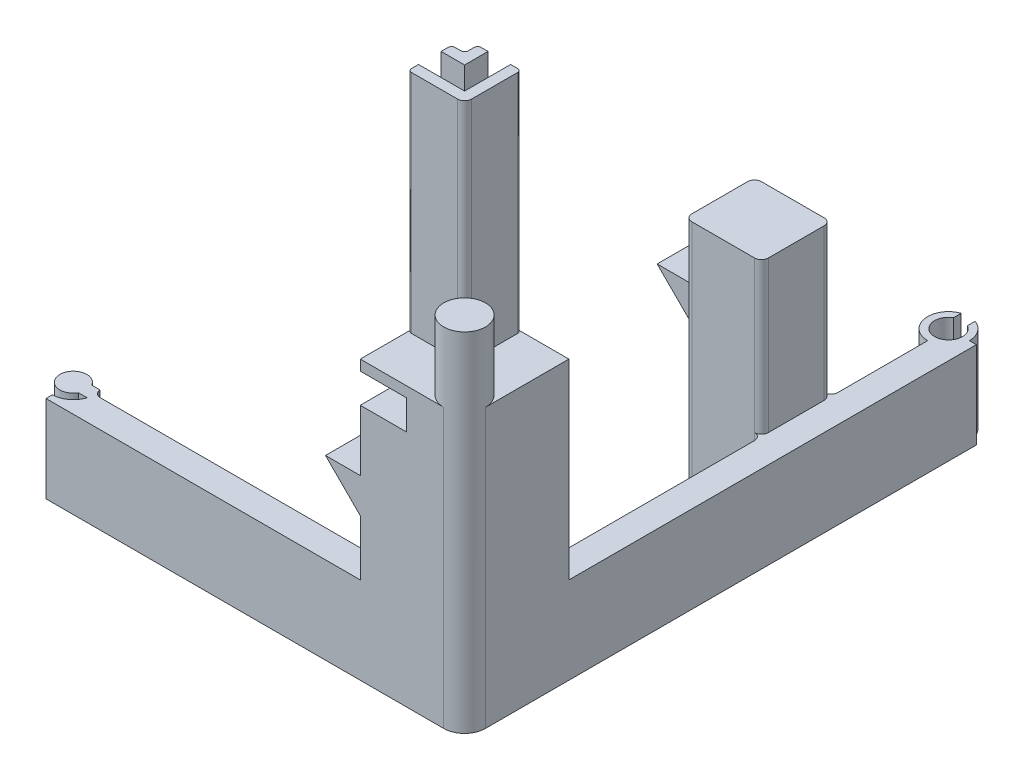
SolidWorks part; units mm, degrees
ref_plane "Front Plane" through (0, 0, 0) normal (0, 0, 1) x (1, 0, 0)
ref_plane "Top Plane" through (0, 0, 0) normal (0, 1, 0) x (1, 0, 0)
ref_plane "Right Plane" through (0, 0, 0) normal (1, 0, 0) x (0, 0, -1)
sketch "Sketch1" plane through (0, 0, 0) normal (0, 1, 0) x (1, 0, 0)
  line L1 (-15, -15) -> (15, -15)
  line L2 (-15, -15) -> (-15, 15)
  line L3 (-15, 15) -> (15, 15)
  line L4 (15, -15) -> (15, 15)
  line L5 (-15, -15) -> (15, 15) construction
  line L6 (-15, 15) -> (15, -15) construction
  point P0 (0, 0)
  dimension "D1" = 30
extrude "Boss-Extrude1" add sketch "Sketch1" along normal blind 80
sketch "Sketch2" plane through (0, 80, 0) normal (0, 1, 0) x (1, 0, 0)
  line L0 (-15, -15) -> (15, -15) construction
  line L1 (15, -15) -> (15, 15) construction
  circle A0 centre (9, -9) radius 6
  dimension "D1" = 12
extrude "Boss-Extrude2" add sketch "Sketch2" along normal blind 20
sketch "Sketch3" plane through (0, 80, 0) normal (0, 1, 0) x (1, 0, 0)
  line L2 (9, -15) -> (15, -15)
  line L4 (15, -15) -> (15, -9)
  circle A1 centre (9, -9) radius 6
  arc A4 (9, -15) -> (15, -9) centre (9, -9) ccw
  dimension "D1" = 0
extrude "Cut-Extrude1" cut sketch "Sketch3" against normal through all
sketch "Sketch4" plane through (0, 80, 0) normal (0, 1, 0) x (1, 0, 0)
  line L16 (-11.25, 1.75) -> (-1.75, 1.75)
  line L17 (-11.25, 11.25) -> (-8.25, 11.25) construction
  line L19 (-11.25, 11.25) -> (-11.25, 8.25) construction
  line L20 (-11.25, 8.25) -> (-8.25, 8.25)
  line L21 (-8.25, 11.25) -> (-8.25, 8.25)
  line L23 (-1.75, 1.75) -> (-1.75, 11.25)
  line L25 (-1.75, 11.25) -> (1.25, 11.25) construction
  line L26 (1.25, 11.25) -> (1.25, -1.25)
  line L27 (1.25, -1.25) -> (-11.25, -1.25)
  line L28 (-11.25, -1.25) -> (-11.25, 1.75) construction
  line L29 (-11.25, 1.75) -> (-11.25, 8.25) construction
  line L30 (-8.25, 11.25) -> (-1.75, 11.25) construction
  line L31 (-11.25, 11.25) -> (-11.25, 15) construction
  line L32 (15, 15) -> (-15, 15) construction
  line L33 (-11.25, 11.25) -> (-15, 11.25) construction
  line L34 (-15, 15) -> (-15, -15) construction
  line L35 (1.25, 11.25) -> (1.25, 15)
  line L36 (1.25, 15) -> (-1.75, 15)
  line L37 (-1.75, 15) -> (-1.75, 11.25)
  line L38 (-11.25, 1.75) -> (-15, 1.75)
  line L39 (-15, 1.75) -> (-15, -1.25)
  line L40 (-15, -1.25) -> (-11.25, -1.25)
  line L41 (-8.25, 11.25) -> (-8.25, 15)
  line L42 (-8.25, 15) -> (-11.25, 15)
  line L43 (-11.25, 15) -> (-11.25, 11.25)
  line L44 (-15, 11.25) -> (-15, 8.25)
  line L45 (-15, 8.25) -> (-11.25, 8.25)
  line L46 (-11.25, 11.25) -> (-15, 11.25)
  dimension "D1" = 6.5
  dimension "D2" = 3
  dimension "D3" = 3.75
extrude "Boss-Extrude3" add sketch "Sketch4" along normal blind 65
sketch "Sketch6" plane through (0, 0, 0) normal (0, -1, 0) x (1, 0, 0)
  line L1 (15, -15) -> (7, -15)
  line L2 (15, -15) -> (15, -132.175)
  line L3 (15, -132.175) -> (13, -132.175)
  line L4 (7, -15) -> (7, -126.175)
  arc A1 (7, -126.175) -> (13, -132.175) centre (7, -132.175) ccw
  dimension "D3" = 12
  dimension "D1" = 117.175
  dimension "D2" = 8
extrude "Boss-Extrude5" add sketch "Sketch6" against normal blind 2
sketch "Sketch7" plane through (0, 2, 0) normal (0, 1, 0) x (1, 0, 0)
  line L0 (7, 136.175) -> (7, 138.175) construction
  line L1 (9, 137.8319) -> (9, 135.6391)
  line L2 (5, 137.8319) -> (5, 135.6391)
  line L3 (7, 128.175) -> (7, 126.175) construction
  line L4 (15, 132.175) -> (13, 132.175)
  line L5 (15, 132.175) -> (15, 15)
  line L6 (15, 15) -> (7, 15)
  line L7 (7, 15) -> (7, 126.175) construction
  line L8 (15, 15) -> (1.25, 15) construction
  line L9 (7, 15) -> (7, 126.175)
  arc A0 (5, 137.8319) -> (7, 126.175) centre (7, 132.175) ccw
  arc A1 (13, 132.175) -> (7, 126.175) centre (7, 132.175) ccw construction
  arc A2 (5, 135.6391) -> (9, 135.6391) centre (7, 132.175) ccw
  arc A3 (13, 132.175) -> (9, 137.8319) centre (7, 132.175) ccw
  dimension "D1" = 2
  dimension "D2" = 2
extrude "Boss-Extrude6" add sketch "Sketch7" along normal offset from surface (23 mm away) 25 up to face at (3.75, 0, -48.4406)
sketch "Sketch9" plane through (0, 0, 0) normal (0, -1, 0) x (1, 0, 0)
  line L0 (15, -15) -> (7, -15) construction
  line L1 (-15, 15) -> (-105.5, 15) construction
  line L2 (-15, 15) -> (-15, 7)
  line L3 (-15, 7) -> (-99.5, 7) construction
  line L4 (-105.5, 15) -> (-105.5, 13.1746) construction
  line L5 (-109.375, 7) -> (-109.5, 7) construction
  line L6 (-101.5, 7) -> (-99.5, 7) construction
  line L7 (-99.5, 9) -> (-102.181, 9) construction
  line L8 (7, -136.175) -> (7, -138.175) construction
  line L9 (9, -137.8319) -> (5, -137.8319) construction
  line L10 (-99.5, 5) -> (-102.181, 5) construction
  line L11 (-99.5, 9) -> (-99.5, 5) construction
  line L12 (-102.1228, 8.9) -> (-99.625, 8.9)
  line L13 (-102.1228, 5.1) -> (-99.5, 5.1) construction
  line L14 (-99.5, 5.1) -> (-99.5, 7) construction
  line L15 (-99.5, 8.9) -> (-99.625, 8.9) construction
  line L16 (-105.375, 15) -> (-105.375, 13.1733)
  line L17 (-105.375, 14.0867) -> (-105.5, 14.0873) construction
  line L18 (-105.375, 15) -> (-15, 15)
  line L19 (-99.5, 5.1) -> (-99.5, 7) construction
  line L20 (-15, 7) -> (-99.5, 7)
  line L21 (-99.8088, 5.1) -> (-102.1228, 5.1)
  circle A0 centre (-105.5, 7) radius 4 construction
  arc A1 (9, -135.6391) -> (5, -135.6391) centre (7, -132.175) ccw construction
  arc A2 (-102.1228, 8.9) -> (-102.1228, 5.1) centre (-105.5, 7) ccw
  arc A4 (-99.625, 8.9) -> (-105.5, 13.1746) centre (-105.5, 7) ccw construction
  arc A6 (-99.625, 8.9) -> (-105.375, 13.1733) centre (-105.5, 7) ccw
  arc A7 (-99.8088, 5.1) -> (-99.5, 7) centre (-105.5, 7) ccw
  arc A8 (7, -126.175) -> (5, -137.8319) centre (7, -132.175) ccw construction
  dimension "D1" = 90.5
  dimension "D2" = 0.125
  dimension "D3" = 1.9
extrude "Boss-Extrude7" add sketch "Sketch9" against normal blind 25
fillet "Fillet1" radius 2 1 edges at (-99.5, 12.5, 7)
sketch "Sketch11" plane through (0, 0, 0) normal (0, -1, 0) x (1, 0, 0)
  line L0 (-99.625, 8.9) -> (-99.75, 8.9) construction
  line L2 (-99.625, 8.9) -> (-102.1228, 8.9) construction
  line L3 (-109.375, 7) -> (-109.5, 7) construction
  circle A0 centre (-105.5, 7) radius 6.0558
  arc A5 (-102.1228, 8.9) -> (-102.1228, 5.1) centre (-105.5, 7) ccw construction
extrude "Cut-Extrude2" cut sketch "Sketch11" against normal offset from surface (2.125 mm away) 0.125 up to face at (7, 2, -134.9552) offset beyond the face yes
sketch "Sketch13" plane through (0, 0, 15) normal (0, 0, 1) x (1, 0, 0)
  line L0 (-15, 80) -> (-15, 25) construction
  line L1 (-15, 68.5) -> (-1.75, 68.5)
  line L2 (-15, 68.5) -> (-15, 77)
  line L3 (-15, 77) -> (-1.75, 77)
  line L4 (-1.75, 68.5) -> (-1.75, 77)
  line L7 (-15, 80) -> (9, 80) construction
  line L9 (-1.75, 145) -> (-1.75, 80) construction
  dimension "D1" = 3
  dimension "D2" = 8.5
extrude "Cut-Extrude4" cut sketch "Sketch13" against normal through all both and the other way through all
sketch "Sketch14" plane through (15, 0, 0) normal (1, 0, 0) x (0, 0, -1)
  line L0 (138.175, 0) -> (-15, 0) construction
fillet "Fillet2" radius 2 1 edges at (1.25, 112.5, 1.25)
sketch "Sketch16" plane through (0, 80, 0) normal (0, 1, 0) x (1, 0, 0)
  line L4 (-15, 11.25) -> (-11.25, 11.25)
  line L5 (-11.25, 11.25) -> (-11.25, 15)
  line L6 (-11.25, 15) -> (-15, 15)
  line L7 (-15, 15) -> (-15, 11.25)
  line L8 (-15, 11.25) -> (-11.25, 11.25)
  line L9 (-11.25, 11.25) -> (-11.25, 15)
  line L10 (-11.25, 15) -> (-15, 15)
  line L11 (-15, 15) -> (-15, 11.25)
  dimension "D1" = 0
extrude "Cut-Extrude6" cut sketch "Sketch16" against normal up to next
fillet "Fillet4" radius 1 5 edges at (-11.25, 111, -15) (-11.25, 111, -11.25) (-15, 111, -11.25) (-15, 112.5, 1.25) (1.25, 112.5, -15)
sketch "Sketch17" plane through (0, 0, 0) normal (0, -1, 0) x (1, 0, 0)
  line L0 (7, -15) -> (7, -126.175) construction
  line L1 (7, -78.3813) -> (-15, -78.3813)
  line L2 (7, -78.3813) -> (7, -98.3813)
  line L3 (7, -98.3813) -> (-15, -98.3813)
  line L4 (-15, -78.3813) -> (-15, -98.3813)
  line L5 (-15, -15) -> (-15, 7) construction
  line L6 (7, -126.175) -> (7, -70.5875) construction
  arc A0 (7, -126.175) -> (13, -132.175) centre (7, -132.175) ccw construction
  point P13 (7, -98.3813)
  dimension "D1" = 20
extrude "Boss-Extrude8" add sketch "Sketch17" against normal up to surface (68.5 mm away) up to face at (-8.375, 68.5, 0)
sketch "Sketch18" plane through (0, 0, 0) normal (0, -1, 0) x (1, 0, 0)
  line L0 (-4, -80.8813) -> (-4, -78.3813) construction
  line L1 (-12.5, -80.8813) -> (4.5, -80.8813)
  line L2 (-12.5, -80.8813) -> (-12.5, -95.8813)
  line L3 (-12.5, -95.8813) -> (4.5, -95.8813)
  line L4 (4.5, -80.8813) -> (4.5, -95.8813)
  line L5 (7, -78.3813) -> (-15, -78.3813) construction
  line L7 (4.5, -88.3813) -> (7, -88.3813) construction
  line L8 (7, -78.3813) -> (7, -98.3813) construction
  dimension "D1" = 2.5
extrude "Cut-Extrude7" cut sketch "Sketch18" against normal offset from surface (66 mm away) 2.5 up to face at (-4, 68.5, -88.3813)
fillet "Fillet5" radius 2 4 edges at (7, 12.5, -78.3813) (7, 12.5, -98.3813) (-15, 34.25, -98.3813) (-15, 34.25, -78.3813)
fillet "Fillet6" radius 2 2 edges at (7, 46.75, -78.3813) (7, 46.75, -98.3813)
chamfer "Chamfer1" distance 7 angle 45 4 edges at (-4, 66, -80.8813) (4.5, 66, -88.3813) (-4, 66, -95.8813) (-12.5, 66, -88.3813)
sketch "Sketch19" plane through (0, 0, 15) normal (0, 0, 1) x (1, 0, 0)
  line L0 (-15, 51) -> (-25, 51)
  line L1 (-15, 68.5) -> (-15, 25) construction
  line L2 (-25, 51) -> (-15, 41)
  line L3 (-15, 41) -> (-15, 51)
  line L4 (-1.75, 68.5) -> (-15, 68.5) construction
  dimension "D1" = 17.5
  dimension "D2" = 10
extrude "Boss-Extrude9" add sketch "Sketch19" against normal up to surface (30 mm away) up to face at (-1.8437, 77.5625, -15)
ref_plane "Plane1" through (0, 0, -88.3813) normal (0, 0, -1) x (-1, 0, 0)
sketch "Sketch20" plane through (0, 0, -88.3813) normal (0, 0, -1) x (-1, 0, 0)
  line L3 (25, 51) -> (15, 51)
  line L4 (15, 41) -> (25, 51)
  line L5 (15, 51) -> (15, 41)
  line L6 (25, 51) -> (15, 51)
  line L7 (15, 41) -> (25, 51)
  line L8 (15, 51) -> (15, 41)
  dimension "D1" = 0
extrude "Boss-Extrude10" add sketch "Sketch20" against normal up to vertex and the other way up to vertex
